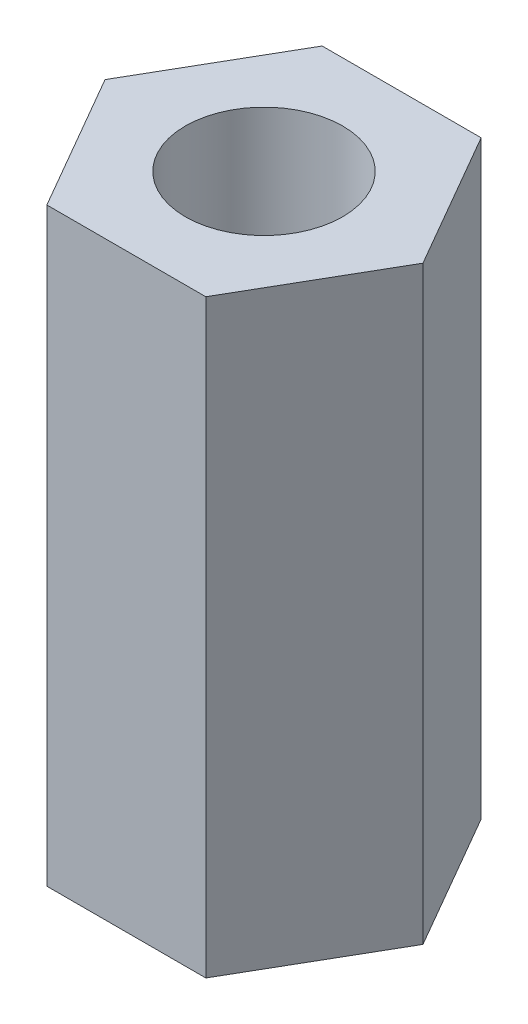
SolidWorks part; units mm, degrees
material "黄铜"
ref_plane "前视基准面" through (0, 0, 0) normal (0, 0, 1) x (1, 0, 0)
ref_plane "上视基准面" through (0, 0, 0) normal (0, 1, 0) x (1, 0, 0)
ref_plane "右视基准面" through (0, 0, 0) normal (1, 0, 0) x (0, 0, -1)
sketch "草图1" plane through (0, 0, 0) normal (0, 1, 0) x (1, 0, 0)
  line L1 (4.0415, 0) -> (2.0207, 3.5)
  line L2 (2.0207, 3.5) -> (-2.0207, 3.5)
  line L3 (-2.0207, 3.5) -> (-4.0415, 0)
  line L4 (-4.0415, 0) -> (-2.0207, -3.5)
  line L5 (-2.0207, -3.5) -> (2.0207, -3.5)
  line L6 (2.0207, -3.5) -> (4.0415, 0)
  circle A0 centre (0, 0) radius 3.5 construction
  circle A1 centre (0, 0) radius 2
  dimension "D1" = 4
  dimension "D2" = 7
extrude "凸台-拉伸1" add sketch "草图1" along normal blind 15
